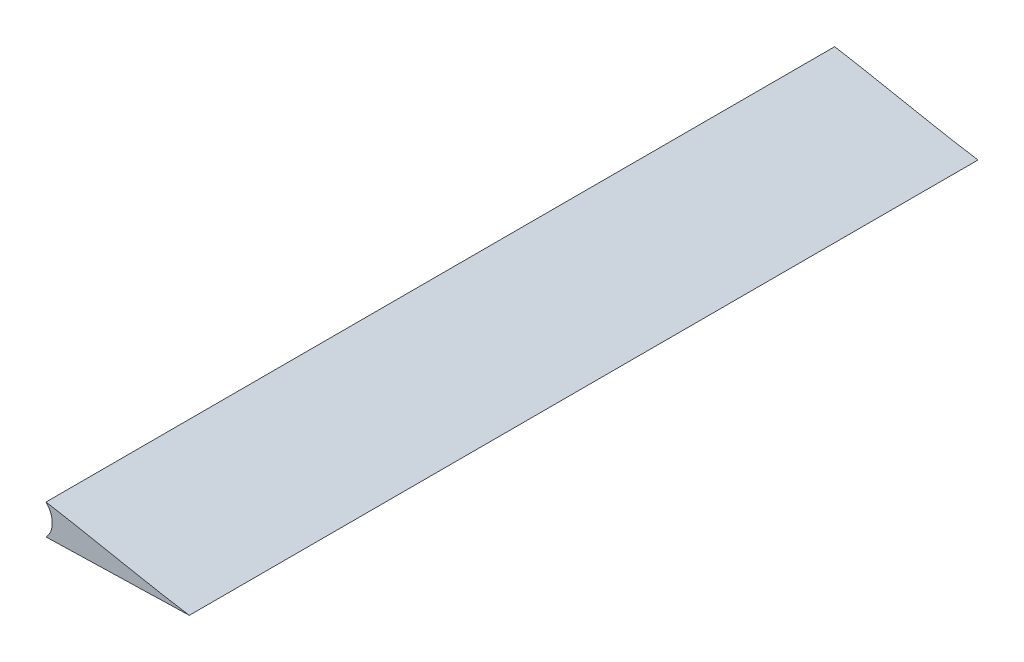
SolidWorks part; units mm, degrees
ref_plane "Front Plane" through (0, 0, 0) normal (0, 0, 1) x (1, 0, 0)
ref_plane "Top Plane" through (0, 0, 0) normal (0, 1, 0) x (1, 0, 0)
ref_plane "Right Plane" through (0, 0, 0) normal (1, 0, 0) x (0, 0, -1)
sketch "Sketch1" plane through (0, 0, 0) normal (0, 0, 1) x (1, 0, 0)
  spline S0 degree 3 poles (100.086, -5.734) (101.1259, -5.7095) (100.1039, -5.6235) (99.2806, -5.4646) (97.3018, -5.1673) (94.8938, -4.7403) (91.7634, -4.194) (88.0758, -3.5271) (83.8259, -2.7338) (79.0747, -1.8292) (73.8683, -0.8153) (68.2576, 0.2815) (62.2977, 1.4477) (56.0406, 2.6595) (49.5223, 3.8633) (42.7762, 5.0242) (35.8425, 6.1594) (28.7549, 7.2252) (21.5571, 8.212) (14.2899, 9.117) (6.9865, 9.8965) (-0.3123, 10.5674) (-7.5733, 11.1015) (-14.7568, 11.4845) (-21.8292, 11.7343) (-28.7564, 11.821) (-35.5035, 11.7506) (-42.0399, 11.5281) (-48.3376, 11.1397) (-54.3688, 10.5993) (-60.1078, 9.9161) (-65.5246, 9.0828) (-70.6007, 8.1336) (-75.3121, 7.0603) (-79.639, 5.8824) (-83.5658, 4.6206) (-87.0746, 3.2865) (-90.1553, 1.9084) (-92.7948, 0.5046) (-94.9831, -0.9044) (-96.7129, -2.2702) (-98.0005, -3.5808) (-98.7619, -4.7432) (-99.2301, -5.8582) (-98.606, -6.8701) (-97.4444, -7.5453) (-95.7467, -8.1886) (-93.4449, -8.653) (-90.5328, -8.9818) (-87.0128, -9.2499) (-82.9066, -9.4712) (-78.2402, -9.5911) (-73.0476, -9.7) (-67.3645, -9.7268) (-61.2329, -9.7356) (-54.6956, -9.664) (-47.7879, -9.5741) (-40.5477, -9.3999) (-33.0149, -9.2242) (-25.2415, -9.0244) (-17.2818, -8.802) (-9.1941, -8.5755) (-1.0348, -8.3896) (7.1349, -8.1639) (15.2619, -7.9372) (23.292, -7.7533) (31.172, -7.5204) (38.8533, -7.3203) (46.2827, -7.155) (53.3967, -6.9428) (60.1348, -6.7644) (66.4618, -6.6108) (72.37, -6.4441) (77.8517, -6.3047) (82.8703, -6.1895) (87.373, -6.0742) (91.2866, -5.9437) (94.6106, -5.8638) (97.1585, -5.8207) (99.2315, -5.7383) (100.086, -5.734) (101.1259, -5.7095) (100.1039, -5.6235) knots -0.008528 -0.003816 -0.00096 0 0.000951 0.003757 0.008317 0.014522 0.022293 0.03156 0.042221 0.054151 0.067231 0.081331 0.096307 0.112012 0.128327 0.145184 0.162488 0.180136 0.198033 0.216059 0.234134 0.252192 0.270104 0.287817 0.305235 0.322284 0.338896 0.354986 0.370506 0.385417 0.399632 0.413116 0.425823 0.437704 0.448737 0.45888 0.468105 0.476405 0.483748 0.490134 0.495557 0.500012 0.503516 0.506001 0.508215 0.511494 0.515844 0.521547 0.528755 0.537449 0.547575 0.559074 0.571867 0.585873 0.60098 0.61708 0.634081 0.651921 0.670484 0.689642 0.709259 0.729201 0.749303 0.769441 0.789466 0.809254 0.82867 0.847598 0.865915 0.883467 0.900079 0.915618 0.930135 0.943663 0.95605 0.967159 0.976853 0.984996 0.991472 0.996184 0.99904 1 1.000951 1.003757 1.008317 only from (100.9182, -5.7031) to (100.9182, -5.7031)
extrude "Boss-Extrude1" add sketch "Sketch1" along normal mid plane 1750
sketch "Sketch3" plane through (0, 0, 0) normal (0, 1, 0) x (1, 0, 0)
  line L0 (100.9182, 835.9) -> (44.3701, 835.9)
  line L2 (100.9182, 524.7075) -> (44.3701, 524.7075)
  line L3 (44.3701, 835.9) -> (44.3701, 524.7075)
  line L4 (100.9182, 875) -> (-99.0734, 875) construction
  line L5 (86.0245, 875) -> (86.5325, 875) construction
  line L8 (-6.5667, 0) -> (6.5667, 0) construction
  line L10 (100.9182, -524.7075) -> (44.3701, -524.7075)
  line L11 (44.3701, -835.9) -> (44.3701, -524.7075)
  line L12 (100.9182, -835.9) -> (44.3701, -835.9)
  line L13 (100.9182, 835.9) -> (100.9182, 941.2715)
  line L14 (100.9182, 941.2715) -> (-134.1332, 941.2715)
  line L15 (-134.1332, 941.2715) -> (-134.1332, -1428.4071)
  line L16 (-134.1332, -1428.4071) -> (100.9182, -1428.4071)
  line L17 (100.9182, -1428.4071) -> (100.9182, -835.9)
  line L18 (100.9182, -524.7075) -> (100.9182, 524.7075)
  dimension "D1" = 311.1925
  dimension "D2" = 56.5481
  dimension "D3" = 39.1
extrude "Cut-Extrude1" cut sketch "Sketch3" against normal through all both and the other way through all
delete or keep bodies "Body-Delete/Keep 1" type delete bodies bodies 103
sketch "Sketch4" plane through (0, 0, -524.7075) normal (0, 0, 1) x (1, 0, 0)
  line L0 (44.3701, 4.7454) -> (44.3701, -7.194)
  arc A0 (44.3701, 4.7454) -> (44.3701, -7.194) centre (38.4004, -1.2243) cw
extrude "Cut-Extrude2" cut sketch "Sketch4" against normal through all
